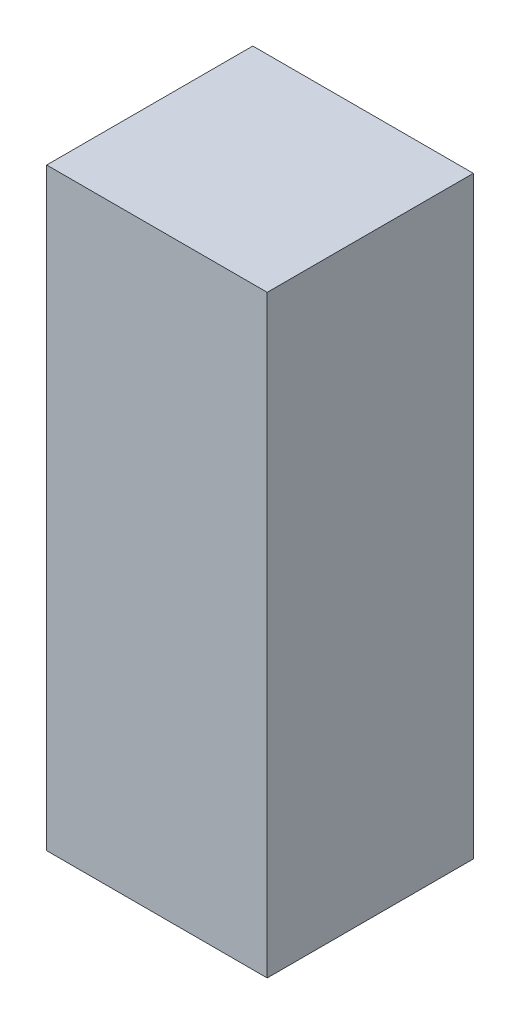
SolidWorks part; units mm, degrees
material "K110"
ref_plane "Front Plane" through (0, 0, 0) normal (0, 0, 1) x (1, 0, 0)
ref_plane "Top Plane" through (0, 0, 0) normal (0, 1, 0) x (1, 0, 0)
ref_plane "Right Plane" through (0, 0, 0) normal (1, 0, 0) x (0, 0, -1)
sketch "Sketch1" plane through (0, 0, 0) normal (0, 1, 0) x (1, 0, 0)
  line L1 (-10.25, -9.58) -> (10.25, -9.58)
  line L2 (-10.25, -9.58) -> (-10.25, 9.58)
  line L3 (-10.25, 9.58) -> (10.25, 9.58)
  line L4 (10.25, -9.58) -> (10.25, 9.58)
  line L5 (-10.25, -9.58) -> (10.25, 9.58) construction
  line L6 (-10.25, 9.58) -> (10.25, -9.58) construction
  point P0 (0, 0)
  dimension "D1" = 19.16
  dimension "D2" = 20.5
extrude "Boss-Extrude1" add sketch "Sketch1" against normal blind 55.2
